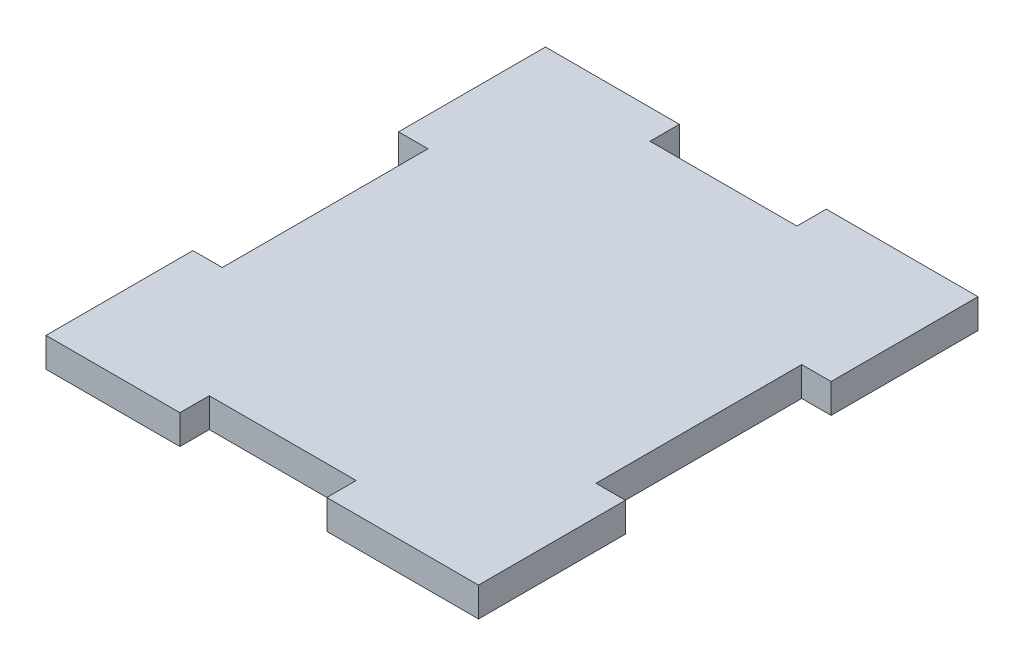
SolidWorks part; units mm, degrees
ref_plane "Front Plane" through (0, 0, 0) normal (0, 0, 1) x (1, 0, 0)
ref_plane "Top Plane" through (0, 0, 0) normal (0, 1, 0) x (1, 0, 0)
ref_plane "Right Plane" through (0, 0, 0) normal (1, 0, 0) x (0, 0, -1)
sketch "Sketch1" plane through (0, 0, 0) normal (0, 1, 0) x (1, 0, 0)
  line L1 (0, 0) -> (76.32, 0)
  line L2 (0, 0) -> (0, 102)
  line L3 (0, 102) -> (76.32, 102)
  line L4 (76.32, 0) -> (76.32, 102)
  dimension "D1" = 102
  dimension "D2" = 76.32
extrude "Boss-Extrude1" add sketch "Sketch1" along normal blind 6
sketch "Sketch2" plane through (76.32, 0, 0) normal (1, 0, 0) x (0, 0, -1)
  line L0 (0, 6) -> (102, 6) construction
  line L1 (0, 0) -> (30, 0)
  line L2 (0, 0) -> (0, 6)
  line L3 (0, 6) -> (30, 6)
  line L4 (30, 0) -> (30, 6)
  dimension "D1" = 30
extrude "Boss-Extrude2" add sketch "Sketch2" along normal blind 6
pattern_linear "LPattern1" count 2 spacing 72 along (0, 0, -1) of "Boss-Extrude2"
sketch "Sketch4" plane through (0, 0, 0) normal (-1, 0, 0) x (0, 0, 1)
  line L0 (-102, 6) -> (0, 6) construction
  line L1 (-102, 0) -> (-72, 0)
  line L2 (-102, 0) -> (-102, 6)
  line L3 (-102, 6) -> (-72, 6)
  line L4 (-72, 0) -> (-72, 6)
  dimension "D1" = 30
extrude "Boss-Extrude3" add sketch "Sketch4" along normal blind 6
pattern_linear "LPattern2" count 2 spacing 72 along (0, 0, 1) of "Boss-Extrude3"
sketch "Sketch5" plane through (0, 0, 0) normal (0, 0, 1) x (1, 0, 0)
  line L0 (-6, 0) -> (82.32, 0) construction
  line L1 (21.34, 0) -> (51.34, 0)
  line L2 (21.34, 0) -> (21.34, 6)
  line L3 (21.34, 6) -> (51.34, 6)
  line L4 (51.34, 0) -> (51.34, 6)
  line L5 (-6, 6) -> (82.32, 6) construction
  line L6 (-6, 0) -> (-6, 6) construction
  dimension "D1" = 27.34
  dimension "D2" = 30
extrude "Cut-Extrude1" cut sketch "Sketch5" against normal blind 6
ref_plane "Plane1" through (0, 0, -51) normal (0, 0, -1) x (-1, 0, 0)
mirror "Mirror1" about plane through (0, 0, -51) normal (0, 0, -1) of "Cut-Extrude1"
